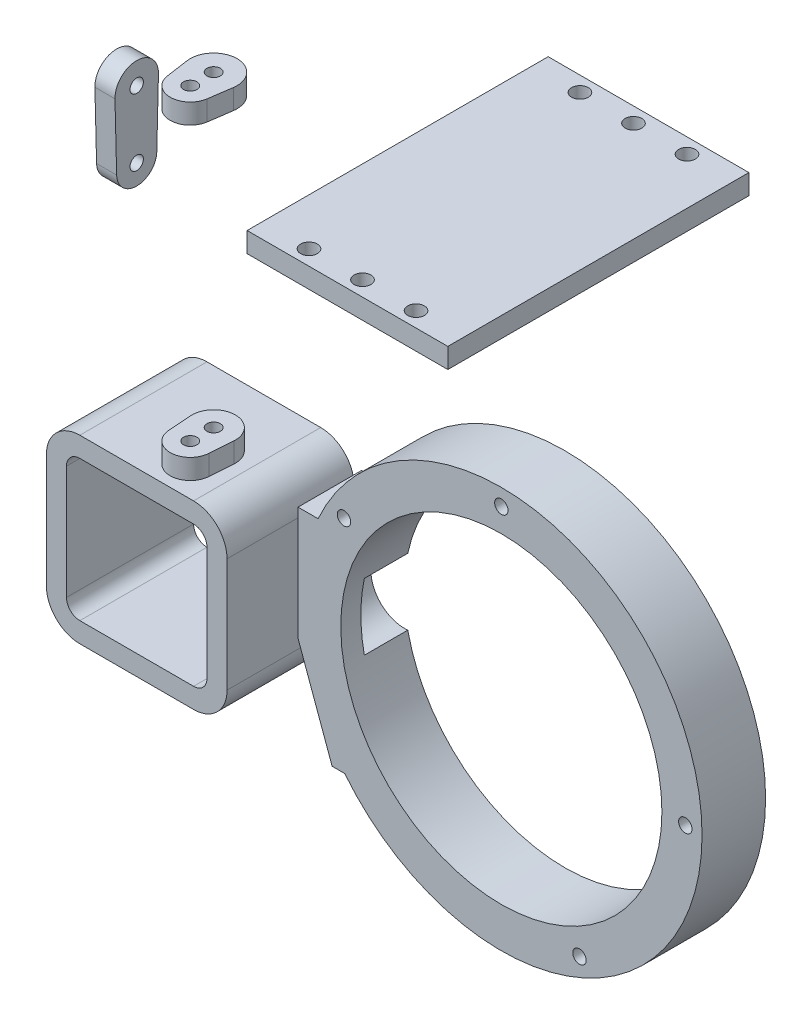
SolidWorks part; units mm, degrees
ref_plane "Front Plane" through (0, 0, 0) normal (0, 0, 1) x (1, 0, 0)
ref_plane "Top Plane" through (0, 0, 0) normal (0, 1, 0) x (1, 0, 0)
ref_plane "Right Plane" through (0, 0, 0) normal (1, 0, 0) x (0, 0, -1)
sketch "Sketch1" plane through (0, 22.5, 0) normal (0, 1, 0) x (1, 0, 0)
  line L4 (24, -6) -> (54, -6)
  line L5 (54, -6) -> (54, 39)
  line L6 (54, 39) -> (24, 39)
  line L7 (24, 39) -> (24, -6)
  line L8 (24, -6) -> (54, -6)
  line L9 (54, -6) -> (54, 39)
  line L10 (54, 39) -> (24, 39)
  line L11 (24, 39) -> (24, -6)
  circle A12 centre (47, -3.75) radius 1.25 construction
  circle A13 centre (39, -3.75) radius 1.25 construction
  circle A14 centre (31, -3.75) radius 1.25 construction
  circle A15 centre (47, 36.75) radius 1.25 construction
  circle A16 centre (39, 36.75) radius 1.25 construction
  circle A17 centre (31, 36.75) radius 1.25 construction
  circle A18 centre (47, -3.75) radius 1.25
  circle A19 centre (39, -3.75) radius 1.25
  circle A20 centre (31, -3.75) radius 1.25
  circle A21 centre (47, 36.75) radius 1.25
  circle A22 centre (39, 36.75) radius 1.25
  circle A23 centre (31, 36.75) radius 1.25
  dimension "D1" = 0
extrude "LASER IF" add sketch "Sketch1" along normal blind 3
sketch "Sketch2" plane through (0, 0, -24) normal (0, 0, 1) x (1, 0, 0)
  line L4 (14.113, -27) -> (11.113, -27)
  line L5 (11.113, -27) -> (11.113, -44)
  line L6 (11.113, -44) -> (16.2086, -58)
  line L7 (16.2086, -58) -> (18.0849, -58)
  line L8 (14.113, -27) -> (11.113, -27)
  line L9 (11.113, -27) -> (11.113, -44)
  line L10 (11.113, -44) -> (16.2086, -58)
  line L11 (16.2086, -58) -> (18.0849, -58)
  arc A0 (18.0208, -44.2183) -> (18.0208, -34.2727) centre (41.5, -39.2455) ccw construction
  arc A1 (18.0849, -58) -> (14.113, -27) centre (41.5, -39.2455) ccw
  arc A2 (18.0849, -58) -> (14.113, -27) centre (41.5, -39.2455) ccw
  arc A3 (18.0208, -34.2727) -> (18.0208, -44.2183) centre (17.5, -39.2455) ccw construction
  arc A8 (18.0208, -44.2183) -> (18.0208, -34.2727) centre (41.5, -39.2455) ccw
  arc A9 (18.0208, -34.2727) -> (18.0208, -44.2183) centre (17.5, -39.2455) ccw
  circle A14 centre (53.1773, -64.1431) radius 1 construction
  circle A15 centre (69, -39.2455) radius 1 construction
  circle A16 centre (17.9773, -25) radius 1 construction
  circle A17 centre (41.5, -11.7455) radius 1 construction
  circle A18 centre (53.1773, -64.1431) radius 1
  circle A19 centre (69, -39.2455) radius 1
  circle A20 centre (17.9773, -25) radius 1
  circle A21 centre (41.5, -11.7455) radius 1
  dimension "D1" = 0
extrude "FLIR IF" add sketch "Sketch2" along normal blind 6.5 separate body
sketch "Sketch7" plane through (0, 0, -17.5) normal (0, 0, 1) x (1, 0, 0)
  line L4 (14.113, -27) -> (11.113, -27)
  line L5 (11.113, -27) -> (11.113, -44)
  line L6 (11.113, -44) -> (16.2086, -58)
  line L7 (16.2086, -58) -> (18.0849, -58)
  line L8 (14.113, -27) -> (11.113, -27)
  line L9 (11.113, -27) -> (11.113, -44)
  line L10 (11.113, -44) -> (16.2086, -58)
  line L11 (16.2086, -58) -> (18.0849, -58)
  circle A0 centre (41.5, -39.2455) radius 24
  arc A1 (18.0849, -58) -> (14.113, -27) centre (41.5, -39.2455) ccw
  arc A2 (18.0849, -58) -> (14.113, -27) centre (41.5, -39.2455) ccw
  circle A3 centre (53.1773, -64.1431) radius 1 construction
  circle A4 centre (69, -39.2455) radius 1 construction
  circle A5 centre (41.5, -11.7455) radius 1 construction
  circle A6 centre (17.9773, -25) radius 1 construction
  circle A7 centre (53.1773, -64.1431) radius 1
  circle A8 centre (69, -39.2455) radius 1
  circle A9 centre (41.5, -11.7455) radius 1
  circle A10 centre (17.9773, -25) radius 1
  dimension "D1" = 0
extrude "FLIR IF TOP" add sketch "Sketch7" along normal blind 3
sketch "Sketch3" plane through (0, 0, -5) normal (0, 0, 1) x (1, 0, 0)
  line L0 (-14, -29.5) -> (-14, -38) construction
  line L1 (-14, -38) -> (-14, -46.5) construction
  line L6 (-12, -48.5) -> (-3.5, -48.5) construction
  line L7 (-3.5, -48.5) -> (5, -48.5) construction
  line L8 (7, -46.5) -> (7, -38) construction
  line L9 (7, -38) -> (7, -29.5) construction
  line L10 (5, -27.5) -> (-3.5, -27.5) construction
  line L11 (-3.5, -27.5) -> (-12, -27.5) construction
  line L12 (-14, -29.5) -> (-14, -38)
  line L13 (-14, -38) -> (-14, -46.5)
  line L14 (-12, -48.5) -> (-3.5, -48.5)
  line L15 (-3.5, -48.5) -> (5, -48.5)
  line L16 (7, -46.5) -> (7, -38)
  line L17 (7, -38) -> (7, -29.5)
  line L18 (5, -27.5) -> (-3.5, -27.5)
  line L19 (-3.5, -27.5) -> (-12, -27.5)
  line L20 (-17, -29.5) -> (-17, -38)
  line L21 (-17, -38) -> (-17, -46.5)
  line L22 (-12, -51.5) -> (-3.5, -51.5)
  line L23 (-3.5, -51.5) -> (5, -51.5)
  line L24 (10, -46.5) -> (10, -38)
  line L25 (10, -38) -> (10, -29.5)
  line L26 (5, -24.5) -> (-3.5, -24.5)
  line L27 (-3.5, -24.5) -> (-12, -24.5)
  arc A0 (-14, -46.5) -> (-12, -48.5) centre (-12, -46.5) ccw construction
  arc A1 (5, -48.5) -> (7, -46.5) centre (5, -46.5) ccw construction
  arc A6 (7, -29.5) -> (5, -27.5) centre (5, -29.5) ccw construction
  arc A7 (-12, -27.5) -> (-14, -29.5) centre (-12, -29.5) ccw construction
  arc A8 (-14, -46.5) -> (-12, -48.5) centre (-12, -46.5) ccw
  arc A9 (5, -48.5) -> (7, -46.5) centre (5, -46.5) ccw
  arc A10 (7, -29.5) -> (5, -27.5) centre (5, -29.5) ccw
  arc A11 (-12, -27.5) -> (-14, -29.5) centre (-12, -29.5) ccw
  arc A12 (-17, -46.5) -> (-12, -51.5) centre (-12, -46.5) ccw
  arc A13 (5, -51.5) -> (10, -46.5) centre (5, -46.5) ccw
  arc A14 (10, -29.5) -> (5, -24.5) centre (5, -29.5) ccw
  arc A15 (-12, -24.5) -> (-17, -29.5) centre (-12, -29.5) ccw
  dimension "D1" = 3
extrude "LWIR IF" add sketch "Sketch3" against normal blind 19 separate body
sketch "Sketch4" plane through (0, 21.5, 0) normal (0, 1, 0) x (1, 0, 0)
  line L0 (3.4641, 12.5) -> (2.9692, 9.0714)
  line L1 (-2.9692, 9.0714) -> (-3.4641, 12.5)
  circle A0 centre (0, 13) radius 1 construction
  circle A1 centre (0, 9.5) radius 1 construction
  circle A2 centre (0, 13) radius 1
  circle A3 centre (0, 9.5) radius 1
  arc A5 (-2.9692, 9.0714) -> (2.9692, 9.0714) centre (0, 9.5) ccw
  circle A6 centre (0, 13) radius 2.25 construction
  circle A8 centre (0, 9.5) radius 3 construction
  arc A10 (3.4641, 12.5) -> (-3.4641, 12.5) centre (0, 13) ccw
  dimension "D1" = 3.5
  dimension "D2" = 2
extrude "Boss-Extrude4" add sketch "Sketch4" along normal blind 3 separate body
sketch "Sketch5" plane through (-18.5, 0, 0) normal (-1, 0, 0) x (0, 0, 1)
  line L0 (-22.9991, -0.075) -> (-23.249, 9.9188)
  line L1 (-17.0009, -0.075) -> (-16.751, 9.9188)
  circle A0 centre (-20, 0) radius 1 construction
  circle A1 centre (-20, 10) radius 1 construction
  circle A2 centre (-20, 0) radius 1
  circle A3 centre (-20, 10) radius 1
  arc A4 (-22.9991, -0.075) -> (-17.0009, -0.075) centre (-20, 0) ccw
  circle A6 centre (-20, 0) radius 3 construction
  circle A7 centre (-20, 10) radius 3.25
  arc A8 (-16.751, 9.9188) -> (-23.249, 9.9188) centre (-20, 10) ccw
  dimension "D1" = 2
  dimension "D2" = 1
extrude "Boss-Extrude5" add sketch "Sketch5" along normal blind 3 separate body
sketch "Sketch6" plane through (0, -21.5, 0) normal (0, -1, 0) x (1, 0, 0)
  line L0 (-2.1247, -53.0471) -> (0.1566, -48.926)
  line L1 (5.6608, -52.3661) -> (2.9561, -56.2226)
  line L2 (-3.2417, -12.7679) -> (-2.9923, -9.2857)
  line L3 (3.2417, -12.7679) -> (2.9923, -9.2857)
  circle A0 centre (0, -9.5) radius 1 construction
  circle A1 centre (3, -50.5) radius 1
  circle A2 centre (3, -50.5) radius 1
  circle A3 centre (0, -13) radius 1 construction
  circle A4 centre (0.5, -54.5) radius 1 construction
  circle A5 centre (0, -9.5) radius 1
  circle A6 centre (0, -13) radius 1
  circle A7 centre (0.5, -54.5) radius 1
  arc A8 (-2.1247, -53.0471) -> (2.9561, -56.2226) centre (0.5, -54.5) ccw
  circle A15 centre (0, -13) radius 3.25
  arc A16 (-3.2417, -12.7679) -> (3.2417, -12.7679) centre (0, -13) ccw
  circle A17 centre (0.5, -54.5) radius 3 construction
  circle A18 centre (3, -50.5) radius 3.25
  arc A19 (5.6608, -52.3661) -> (0.1566, -48.926) centre (3, -50.5) ccw
  arc A22 (2.9923, -9.2857) -> (-2.9923, -9.2857) centre (0, -9.5) ccw
  dimension "D5" = 3
  dimension "D1" = 0
  dimension "D2" = 2
  dimension "D3" = 1
  dimension "D4" = 1
extrude "Boss-Extrude6" add sketch "Sketch6" along normal blind 3
